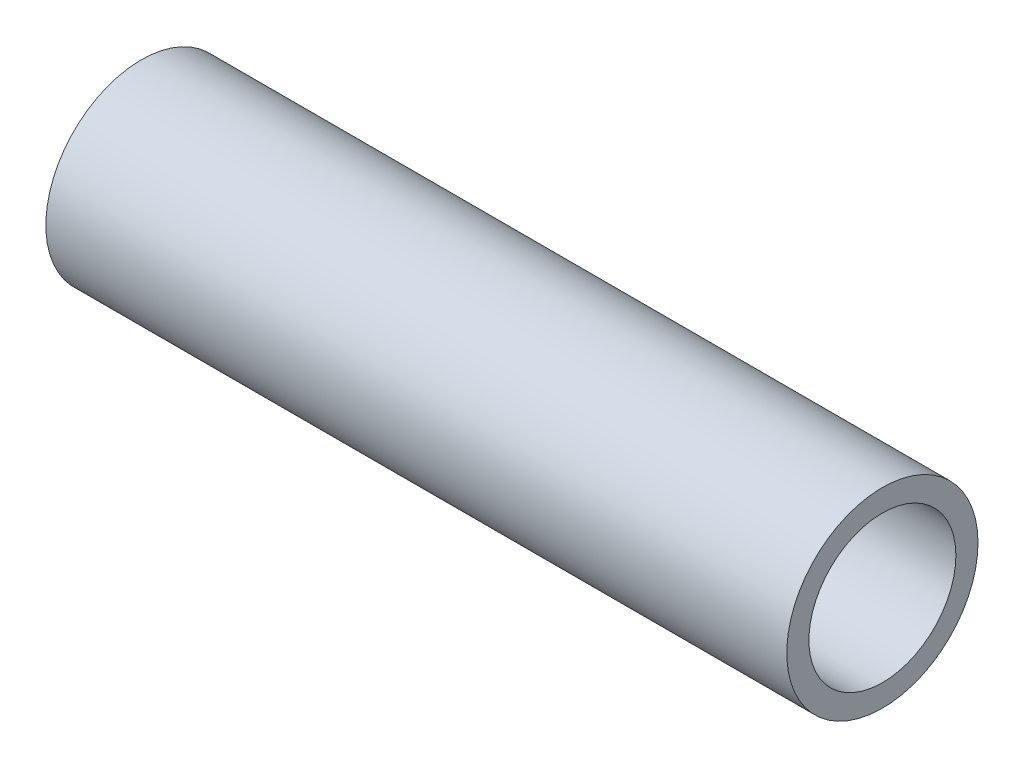
SolidWorks part; units mm, degrees
ref_plane "正面" through (0, 0, 0) normal (0, 0, 1) x (1, 0, 0)
ref_plane "平面" through (0, 0, 0) normal (0, 1, 0) x (1, 0, 0)
ref_plane "右側面" through (0, 0, 0) normal (1, 0, 0) x (0, 0, -1)
sketch "ｽｹｯﾁ1" plane through (0, 0, 0) normal (1, 0, 0) x (0, 0, -1)
  circle A0 centre (0, 0) radius 6.15
  circle A1 centre (0, 0) radius 8
  dimension "D1" = 12.3
  dimension "D2" = 16
extrude "ﾎﾞｽ - 押し出し1" add sketch "ｽｹｯﾁ1" along normal blind 62
equation "\"長さ\" = 62"
equation "\"D1@ﾎﾞｽ - 押し出し1\"=\"長さ\""
